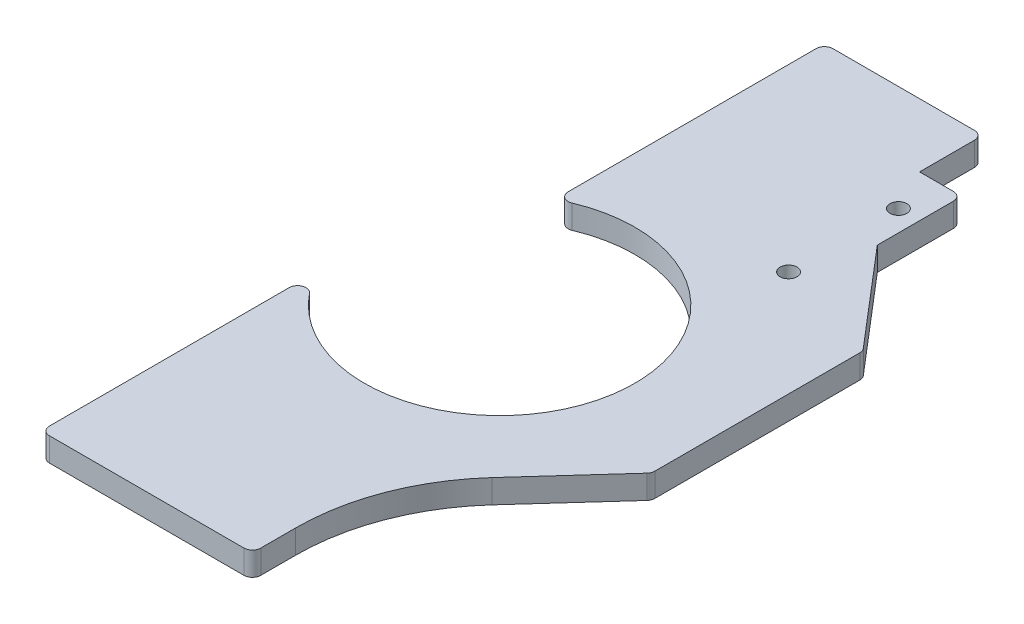
SolidWorks part; units mm, degrees
material "3DP"
ref_plane "正面" through (0, 0, 0) normal (0, 0, 1) x (1, 0, 0)
ref_plane "平面" through (0, 0, 0) normal (0, 1, 0) x (1, 0, 0)
ref_plane "右側面" through (0, 0, 0) normal (1, 0, 0) x (0, 0, -1)
sketch "ｽｹｯﾁ1" plane through (0, 0, 0) normal (0, 1, 0) x (1, 0, 0)
  line L0 (47.5, -35) -> (67.5, -58.4)
  line L1 (0, 0) -> (37.5, 0)
  line L2 (0, 0) -> (0, -63.8082)
  line L4 (47.5, -15) -> (47.5, -35)
  line L5 (47.5, 0) -> (37.5, 0) construction
  line L6 (47.5, 0) -> (47.5, -15) construction
  line L7 (47.5, -15) -> (37.5, -15)
  line L8 (37.5, 0) -> (37.5, -15)
  line L9 (67.5, -58.4) -> (67.5, -108.4)
  line L10 (67.5, -108.4) -> (36.64, -142.4805)
  line L11 (15.14, -92) -> (52.07, -125.4402) construction
  line L12 (36.64, -142.4805) -> (36.64, -172)
  line L13 (36.64, -172) -> (-13.36, -172)
  line L14 (-13.36, -172) -> (-13.36, -106.5516)
  line L15 (47.5, 0) -> (47.5, -15) construction
  line L16 (37.5, 0) -> (47.5, 0) construction
  line L17 (47.5, -35) -> (47.5, -58.4) construction
  line L18 (-13.36, -106.5516) -> (-13.36, -101.3675) construction
  arc A0 (-13.36, -106.5516) -> (0, -63.8082) centre (15.14, -92) ccw
  circle A1 centre (15.14, -92) radius 30 construction
  circle A2 centre (42.5, -25) radius 2
  circle A3 centre (42.5, -51) radius 2
  dimension "D6" = 15.14
  dimension "D7" = 92
  dimension "D8" = 64
  dimension "D13" = 60
  dimension "D15" = 25
  dimension "D16" = 51
  dimension "D17" = 4
  dimension "D18" = 5
  dimension "D1" = 47.5
  dimension "D2" = 58.4
  dimension "D3" = 15
  dimension "D4" = 10
  dimension "D5" = 20
  dimension "D9" = 20
  dimension "D10" = 50
  dimension "D11" = 80
  dimension "D12" = 28.5
  dimension "D14" = 50
extrude "ﾎﾞｽ - 押し出し1" add sketch "ｽｹｯﾁ1" along normal blind 5.6
fillet "ﾌｨﾚｯﾄ1" radius 2 2 edges at (-13.36, 2.8, 106.5516) (0, 2.8, 63.8082)
fillet "ﾌｨﾚｯﾄ2" radius 2 7 edges at (-13.36, 2.8, 172) (36.64, 2.8, 172) (67.5, 2.8, 108.4) (67.5, 2.8, 58.4) (47.5, 2.8, 15) (37.5, 2.8, 0) (0, 2.8, 0)
fillet "ﾌｨﾚｯﾄ3" radius 50 1 edges at (36.64, 2.8, 142.4805)
